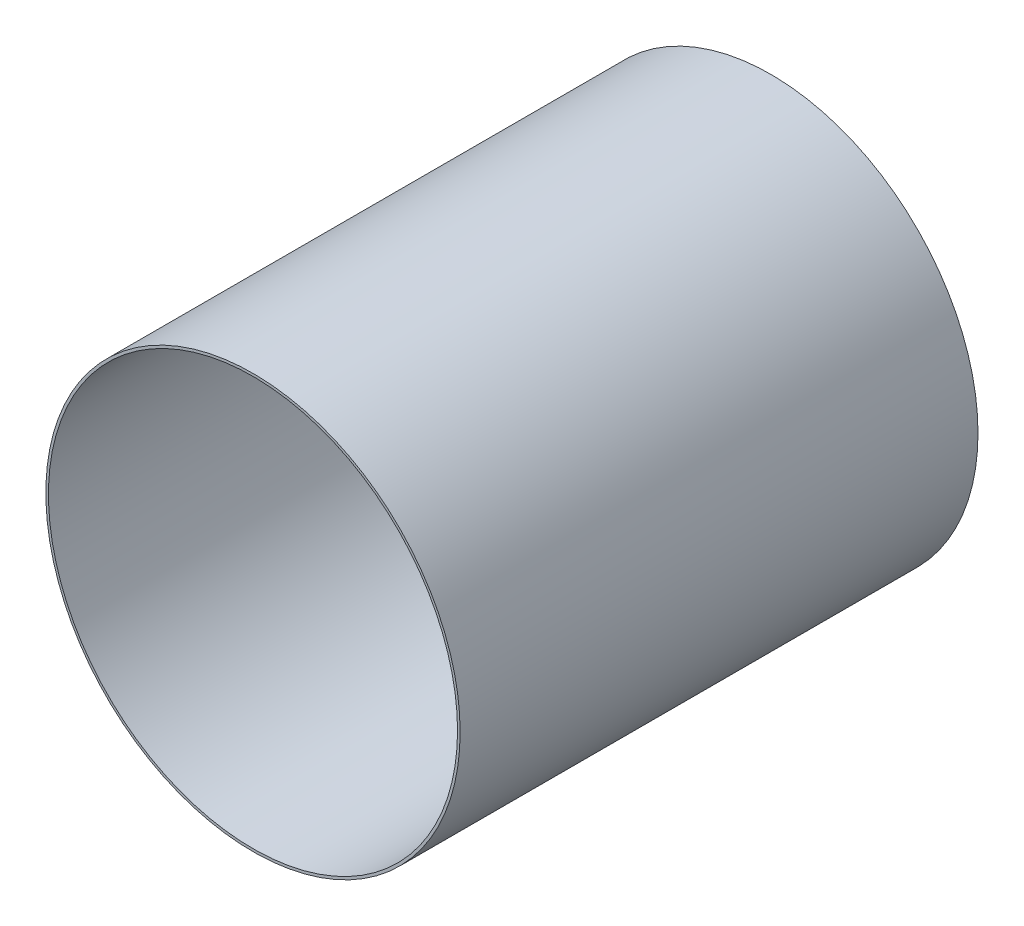
SolidWorks part; units mm, degrees
ref_plane "前视基准面" through (0, 0, 0) normal (0, 0, 1) x (1, 0, 0)
ref_plane "上视基准面" through (0, 0, 0) normal (0, 1, 0) x (1, 0, 0)
ref_plane "右视基准面" through (0, 0, 0) normal (1, 0, 0) x (0, 0, -1)
sketch "草图1" plane through (0, 0, 0) normal (0, 0, 1) x (1, 0, 0)
  circle A0 centre (0, 0) radius 4
  circle A1 centre (0, 0) radius 3.95
  dimension "D1" = 8
  dimension "D2" = 7.9
extrude "凸台-拉伸1" add sketch "草图1" along normal blind 10
